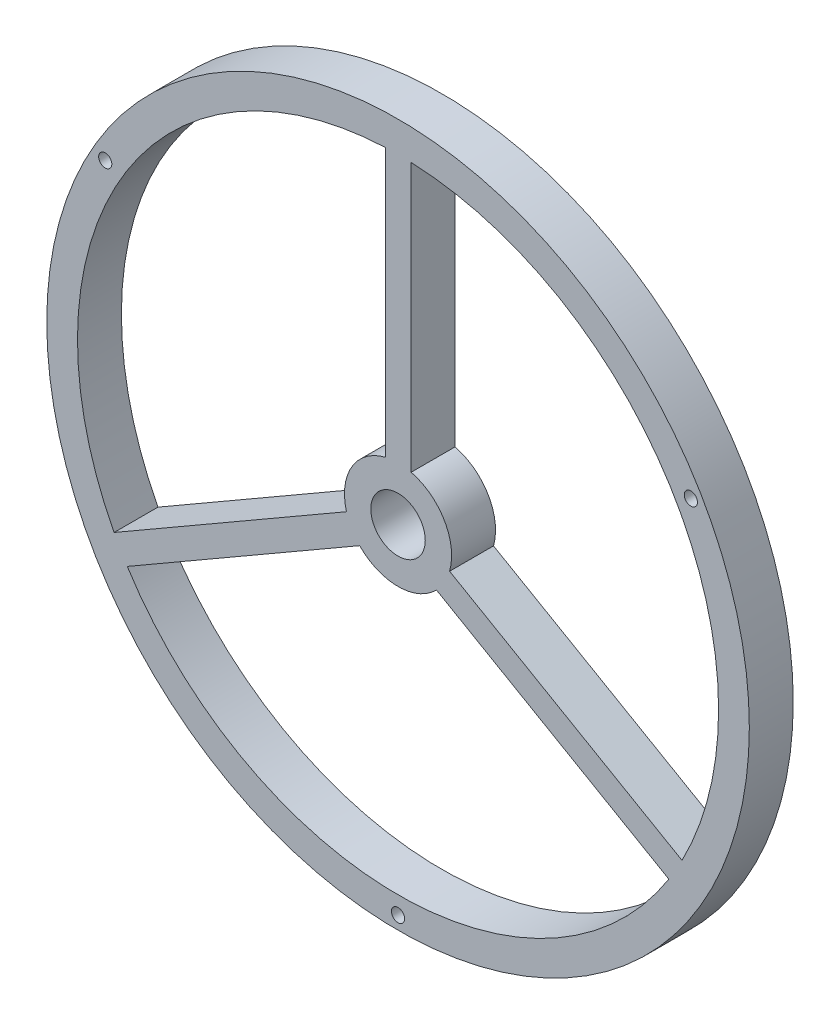
SolidWorks part; units mm, degrees
ref_plane "前视基准面" through (0, 0, 0) normal (0, 0, 1) x (1, 0, 0)
ref_plane "上视基准面" through (0, 0, 0) normal (0, 1, 0) x (1, 0, 0)
ref_plane "右视基准面" through (0, 0, 0) normal (1, 0, 0) x (0, 0, -1)
sketch "草图1" plane through (0, 0, 0) normal (0, 0, 1) x (1, 0, 0)
  line L0 (48.2965, 27.9249) -> (48.2965, 67.9249) construction
  line L1 (48.2965, 27.9249) -> (13.6555, 7.9249) construction
  line L2 (48.2965, 27.9249) -> (82.9375, 7.9249) construction
  line L3 (81.0732, 9.0013) -> (81.8232, 10.3003)
  line L7 (46.8483, 66.0915) -> (46.8483, 32.6388)
  line L11 (49.7879, 66.0915) -> (49.7879, 32.6388)
  line L12 (81.0732, 9.0013) -> (80.3232, 7.7022)
  line L13 (81.8232, 10.3003) -> (52.5654, 27.1923)
  line L14 (52.5654, 27.1923) -> (51.0654, 24.5942)
  line L15 (51.0654, 24.5942) -> (80.3232, 7.7022)
  line L16 (15.5198, 9.0013) -> (14.7698, 10.3003)
  line L17 (15.5198, 9.0013) -> (16.2698, 7.7022)
  line L18 (14.7698, 10.3003) -> (43.9274, 27.1345)
  line L19 (43.9274, 27.1345) -> (45.4274, 24.5364)
  line L20 (45.4274, 24.5364) -> (16.2698, 7.7022)
  line L21 (46.8483, 32.6388) -> (49.7879, 32.6388)
  line L22 (46.8483, 66.0915) -> (49.7879, 66.0915)
  circle A1 centre (48.2965, 27.9249) radius 3.1
  circle A2 centre (48.2965, 27.9249) radius 6.1
  circle A3 centre (48.2965, 27.9249) radius 40
  circle A4 centre (48.2965, 27.9249) radius 36.5
  dimension "D1" = 3
  dimension "D2" = 3.5
extrude "凸台-拉伸2" add sketch "草图1" along normal blind 5 contours A3 A4 L7 L22 L11 L13 L3 L12 L15 L20 L17 L16 L18 | L7 A2 L18 L19 L20 L15 L14 L13 L11 L21 A1 | L18 A4 L20 A2 | A4 L18 L16 L17 L20 | L15 A2 L13 L14 | L11 A2 L7 L21 | L18 A2 L20 L19 | L11 A4 L7 A2 | A4 L11 L22 L7 | A4 L15 L12 L3 L13 | L15 A4 L13 A2
sketch "草图2" plane through (0, 0, 5) normal (0, 0, 1) x (1, 0, 0)
  line L0 (48.2965, 27.9249) -> (14.9545, 47.1749)
  line L1 (48.2965, 27.9249) -> (81.6385, 47.1749)
  line L2 (48.2965, 27.9249) -> (48.2965, -10.5751)
  circle A0 centre (14.9545, 47.1749) radius 0.75
  circle A1 centre (81.6385, 47.1749) radius 0.75
  circle A2 centre (48.2965, -10.5751) radius 0.75
extrude "切除-拉伸1" cut sketch "草图2" against normal blind 5
